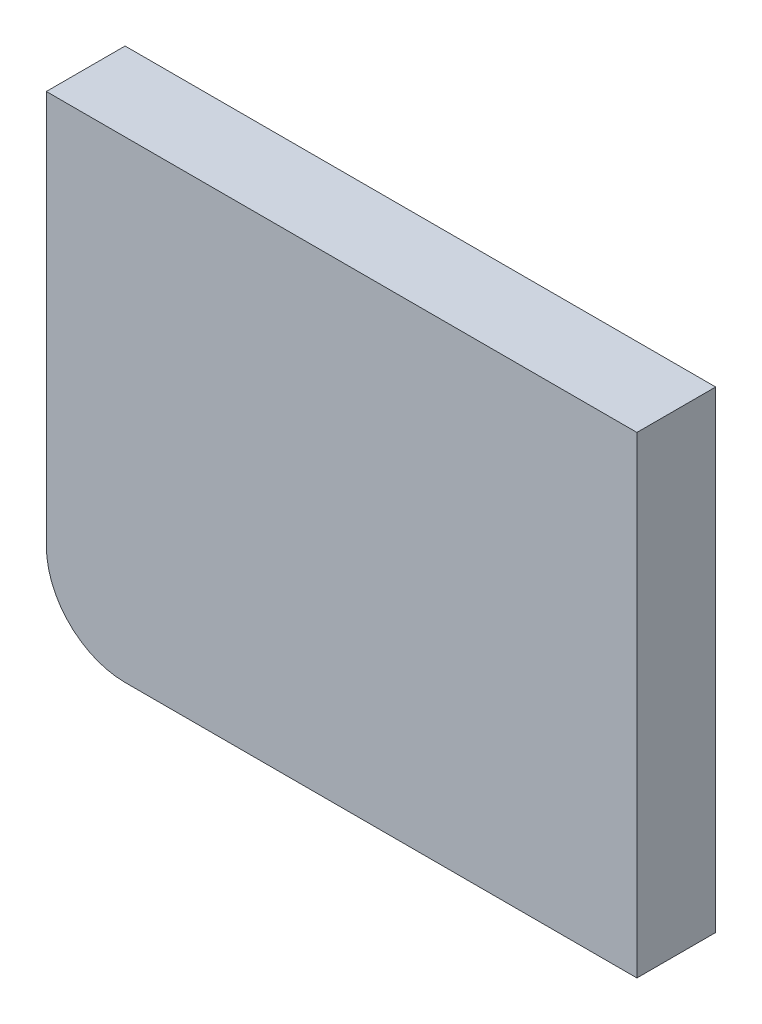
SolidWorks part; units mm, degrees
ref_plane "Front Plane" through (0, 0, 0) normal (0, 0, 1) x (1, 0, 0)
ref_plane "Top Plane" through (0, 0, 0) normal (0, 1, 0) x (1, 0, 0)
ref_plane "Right Plane" through (0, 0, 0) normal (1, 0, 0) x (0, 0, -1)
sketch "Sketch1" plane through (0, 0, 0) normal (0, 0, 1) x (1, 0, 0)
  line L0 (-37.8212, 0) -> (-37.8212, 0.2145) construction
  line L1 (-37.8212, 1) -> (-37.8212, 0.2145) construction
  line L2 (-37.8212, 0.5877) -> (-37.8212, 6) construction
  line L3 (-37.8212, 0) -> (-37.8212, -6) construction
  line L4 (-35.8212, -8) -> (-13.7903, -8) construction
  line L5 (-22.8212, 4) -> (-22.8212, -8) construction
  line L6 (-37.8212, 4) -> (-22.8212, 4) construction
  line L7 (-37.8212, 0) -> (-37.8212, 0.2145)
  line L8 (-37.8212, 1) -> (-37.8212, 0.2145)
  line L9 (-37.8212, 0.5877) -> (-37.8212, 4)
  line L10 (-37.8212, 0) -> (-37.8212, -6)
  line L11 (-35.8212, -8) -> (-22.8212, -8)
  line L12 (-22.8212, 4) -> (-22.8212, -8)
  line L13 (-37.8212, 4) -> (-22.8212, 4)
  arc A0 (-37.8212, -6) -> (-35.8212, -8) centre (-35.8212, -6) ccw construction
  arc A1 (-37.8212, -6) -> (-35.8212, -8) centre (-35.8212, -6) ccw
extrude "Boss-Extrude1" add sketch "Sketch1" along normal blind 2 contours L10 A1 L11 L12 L13 L9 L8 L7
